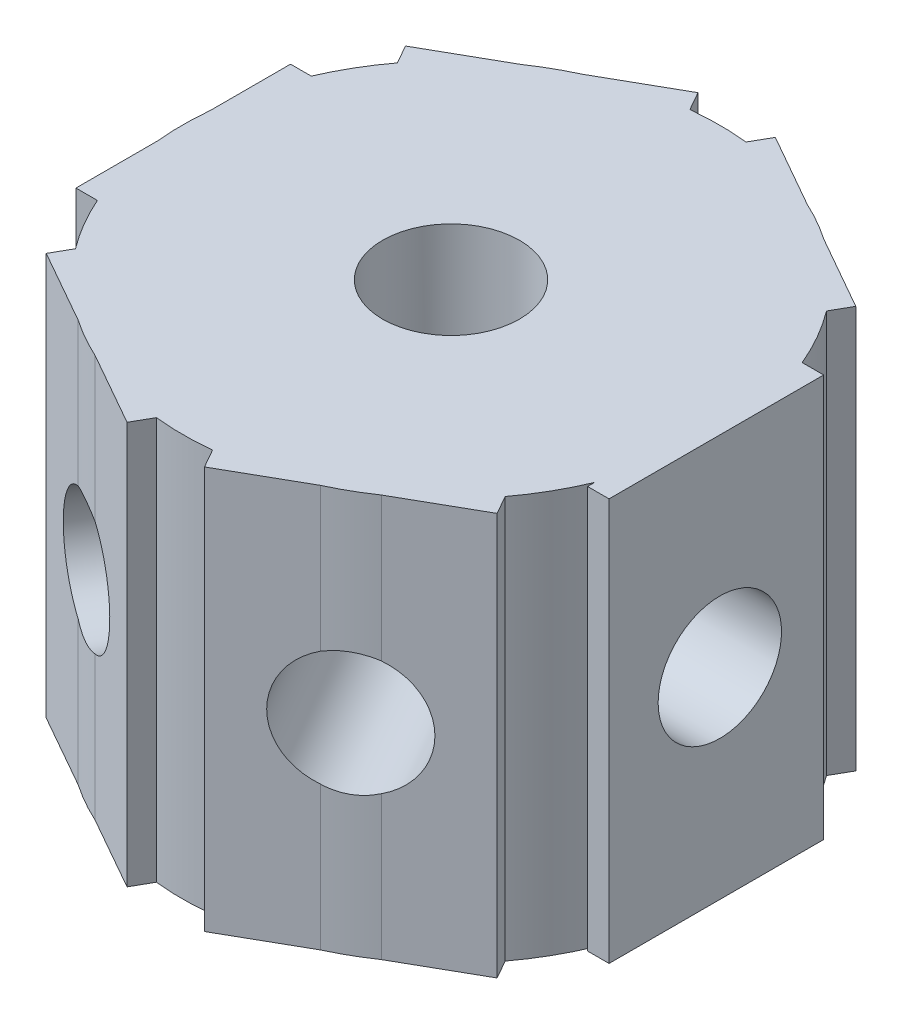
SolidWorks part; units mm, degrees
ref_plane "Front Plane" through (0, 0, 0) normal (0, 0, 1) x (1, 0, 0)
ref_plane "Top Plane" through (0, 0, 0) normal (0, 1, 0) x (1, 0, 0)
ref_plane "Right Plane" through (0, 0, 0) normal (1, 0, 0) x (0, 0, -1)
sketch "Sketch1" plane through (0, 0, 0) normal (0, 1, 0) x (1, 0, 0)
  circle A0 centre (0, 0) radius 3.2385
  circle A1 centre (0, 0) radius 12.7
  dimension "D1" = 6.477
  dimension "D2" = 25.4
extrude "Boss-Extrude1" add sketch "Sketch1" along normal blind 19.05
ref_plane "Plane1" through (0, 9.525, 0) normal (0, -1, 0) x (-1, 0, 0)
sketch3d "3DSketch2"
  circle A0 centre (0, 0, 0) radius 12.7 construction
  circle A1 centre (0, 0, 0) radius 12.7
  point P2 (0, 12.7, 0)
  point P4 (0, 12.7, 0)
sketch "Sketch2" plane through (0, 9.525, 0) normal (0, -1, 0) x (-1, 0, 0)
  circle A0 centre (0, 0) radius 12.7 construction
  circle A1 centre (0, 0) radius 12.7
  circle A2 centre (0, 0) radius 12.7 construction
  circle A3 centre (0, 0) radius 12.7
  circle A4 centre (0, 0) radius 12.7
  point P7 (-12.7, 0)
sketch "Sketch3" plane through (0, 0, 0) normal (0, 0, 1) x (1, 0, 0)
  line L0 (12.7, 19.05) -> (-12.7, 19.05) construction
  point P0 (0, 19.05)
  point P1 (0, 0)
ref_plane "Plane2" through (0, 0, 0) normal (0, 1, 0) x (1, 0, 0)
sketch "Sketch4" plane through (0, 0, 0) normal (0, 1, 0) x (1, 0, 0)
  line L0 (-11.6219, 5.0393) -> (11.7103, 4.9153) construction
  line L2 (-11.6219, -5.1207) -> (11.7103, -5.2447) construction
  line L3 (-10.16, 7.62) -> (1.3382, -12.6293) construction
  line L6 (1.3382, -12.6293) -> (-1.3217, 12.631) construction
  line L15 (11.7103, -5.2447) -> (11.7103, 4.9153)
  line L16 (11.7103, 4.9153) -> (12.7263, 4.9153)
  line L17 (12.7263, 4.9153) -> (12.7263, -5.2447)
  line L18 (12.7263, -5.2447) -> (11.7103, -5.2447)
  line L24 (-11.6219, 5.0393) -> (-11.6219, -5.1207)
  line L28 (-11.6219, -5.1207) -> (-12.6379, -5.1207)
  line L29 (-12.6379, -5.1207) -> (-12.6379, 5.0393)
  line L30 (-12.6379, 5.0393) -> (-11.6219, 5.0393)
  line L36 (-10.16, 7.62) -> (-1.3217, 12.631)
  line L37 (-10.16, 7.62) -> (-10.6611, 8.5038)
  line L38 (-10.6611, 8.5038) -> (-1.8228, 13.5149)
  line L39 (-1.8228, 13.5149) -> (-1.3217, 12.631)
  line L40 (-1.3217, 12.631) -> (10.1699, -7.6068) construction
  line L41 (1.3382, 12.6293) -> (10.1699, 7.6068)
  line L42 (10.1699, 7.6068) -> (10.6722, 8.4899)
  line L43 (10.6722, 8.4899) -> (1.8404, 13.5125)
  line L44 (1.8404, 13.5125) -> (1.3382, 12.6293)
  line L45 (10.1699, -7.6068) -> (10.1699, 7.6068) construction
  line L46 (-10.16, -7.62) -> (-1.3217, -12.631)
  line L47 (-1.3217, -12.631) -> (-1.8228, -13.5149)
  line L48 (-1.8228, -13.5149) -> (-10.6611, -8.5038)
  line L49 (-10.6611, -8.5038) -> (-10.16, -7.62)
  line L50 (-10.16, -7.62) -> (-10.6611, -8.5038)
  line L51 (10.1699, 7.6068) -> (-1.3382, -12.6293) construction
  line L52 (1.3382, -12.6293) -> (10.1699, -7.6068)
  line L53 (10.1699, -7.6068) -> (10.6722, -8.4899)
  line L54 (10.6722, -8.4899) -> (1.8404, -13.5125)
  line L55 (1.8404, -13.5125) -> (1.3382, -12.6293)
  line L56 (10.1699, 7.6068) -> (10.123, 7.6691)
  line L57 (1.3382, 12.6293) -> (-10.16, -7.62) construction
  circle A0 centre (0, 0) radius 12.7 construction
  circle A1 centre (0, 0) radius 12.7 construction
  dimension "D2" = 1.016
  dimension "D3" = 10.16
  dimension "D4" = 1.016
  dimension "D5" = 10.16
  dimension "D6" = 1.016
  dimension "D7" = 1.016
  dimension "D8" = 10.16
  dimension "D9" = 1.016
  dimension "D10" = 1.016
  dimension "D11" = 10.16
  dimension "D12" = 10.16
  dimension "D13" = 10.16
extrude "Boss-Extrude2" add sketch "Sketch4" along normal blind 19.05
ref_plane "Plane3" through (15.2663, 0, 0) normal (1, 0, 0) x (0, 0, -1)
sketch "Sketch5" plane through (15.2663, 0, 0) normal (1, 0, 0) x (0, 0, -1)
  line L0 (0, 26.8622) -> (0, -1.3028) construction
  line L1 (-8.4495, 9.525) -> (4.9153, 9.525) construction
  line L2 (-12.7, 9.525) -> (12.7, 9.525) construction
  line L3 (4.9153, 19.05) -> (4.9153, 0) construction
  point P9 (0, 9.525)
ref_plane "Plane4" through (-15.1779, 0, 0) normal (-1, 0, 0) x (0, 0, 1)
sketch "Sketch8" plane through (-15.1779, 0, 0) normal (-1, 0, 0) x (0, 0, 1)
  circle A0 centre (0, 9.525) radius 2.921
  dimension "D1" = 5.842
extrude "Cut-Extrude1" cut sketch "Sketch8" against normal through all both and the other way through all
ref_plane "Plane5" through (7.5119, 0, -13.2091) normal (0.4943, 0, -0.8693) x (-0.8693, 0, -0.4943)
sketch "Sketch9" plane through (7.5119, 0, -13.2091) normal (0.4943, 0, -0.8693) x (-0.8693, 0, -0.4943)
  line L0 (-12.7, 9.525) -> (12.7, 9.525) construction
  circle A0 centre (0, 9.525) radius 2.921
  dimension "D1" = 5.842
extrude "Cut-Extrude2" cut sketch "Sketch9" against normal through all both
ref_plane "Plane6" through (7.5119, 0, 13.2091) normal (0.4943, 0, 0.8693) x (0.8693, 0, -0.4943)
sketch "Sketch10" plane through (7.5119, 0, 13.2091) normal (0.4943, 0, 0.8693) x (0.8693, 0, -0.4943)
  line L0 (-12.7, 9.525) -> (12.7, 9.525) construction
  circle A0 centre (0, 9.525) radius 2.921
  dimension "D1" = 5.842
extrude "Cut-Extrude3" cut sketch "Sketch10" against normal through all both
